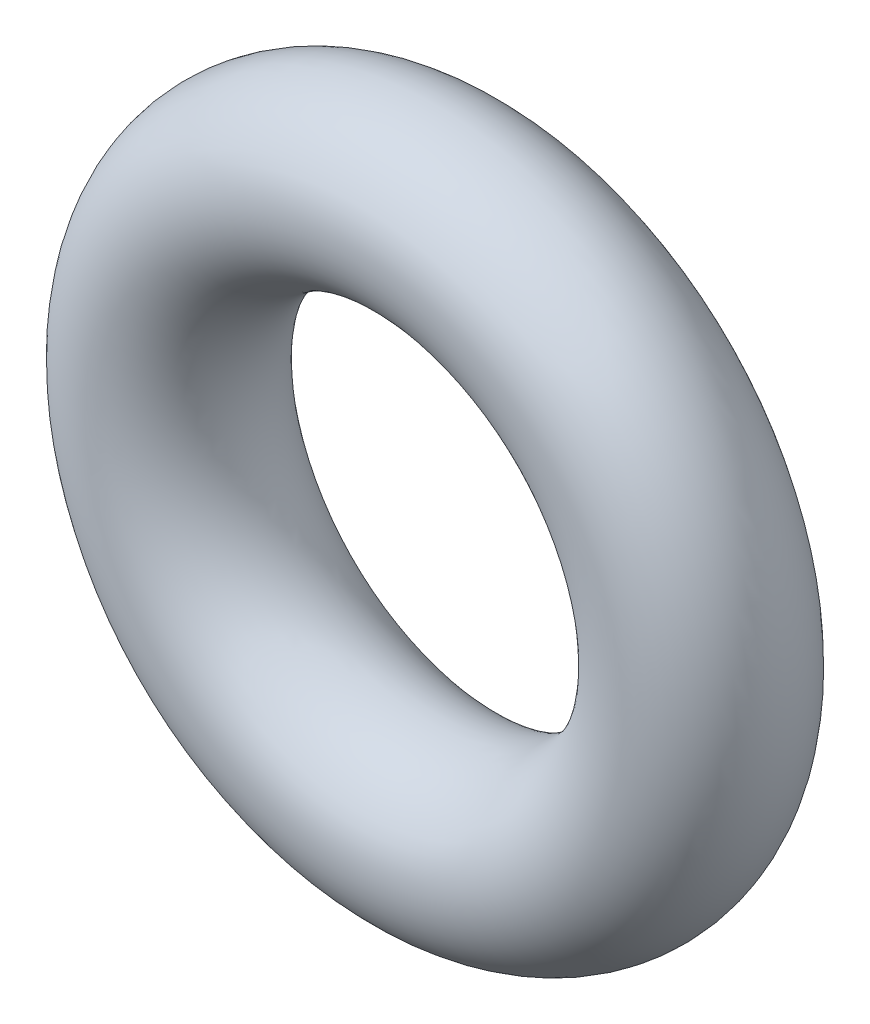
SolidWorks part; units mm, degrees
ref_plane "Front Plane" through (0, 0, 0) normal (0, 0, 1) x (1, 0, 0)
ref_plane "Top Plane" through (0, 0, 0) normal (0, 1, 0) x (1, 0, 0)
ref_plane "Right Plane" through (0, 0, 0) normal (1, 0, 0) x (0, 0, -1)
sketch "Sketch1" plane through (0, 0, 0) normal (0, 0, 1) x (1, 0, 0)
  line L0 (-3.6195, 0) -> (3.6195, 0) construction
  line L1 (-1.8415, 0) -> (1.8415, 0) construction
  line L2 (-2.5594, 2.5594) -> (2.5594, -2.5594) construction
  point P3 (1.8415, 0)
  point P4 (0, 0)
  point P8 (0, 0)
  point P9 (0, 0)
  point P10 (-3.6195, 0)
  point P11 (-1.8415, 0)
  point P14 (0, 0)
  point P15 (2.5594, -2.5594)
  point P16 (3.6195, 0)
  dimension "Actual OD" = 7.239
  dimension "Actual ID" = 3.683
  dimension "Actual Width" = 1.778
  dimension "D1" = 45
sketch "Sketch2" plane through (0, 0, 0) normal (0, 1, 0) x (1, 0, 0)
  line L0 (-3.6195, 0) -> (3.6195, 0) construction
  line L1 (-2.7305, 0.889) -> (-2.7305, -0.889) construction
  line L2 (0, -0.889) -> (0, 0.889) construction
  circle A0 centre (-2.7305, 0) radius 0.889
  point P12 (0, 0)
revolve "Revolve1" add sketch "Sketch2" angle 360 about L2
sketch "Sketch3" plane through (0, 0, 0) normal (1, 0, 0) x (0, 0, -1)
  line L0 (-0.889, 0) -> (0.889, 0) construction
  line L1 (-0.889, -1.3811) -> (-0.889, 1.3811) construction
  point P4 (0, 0)
  point P7 (-0.889, 0)
  point P9 (-0.889, -1.3811)
  dimension "D1" = 1.778
  dimension "D2" = 2.7622
equation "\"D1@Sketch3\"=\"Actual Width@Sketch1\""
equation "\"D2@Sketch3\"=\"Actual ID@Sketch1\"*.75"
